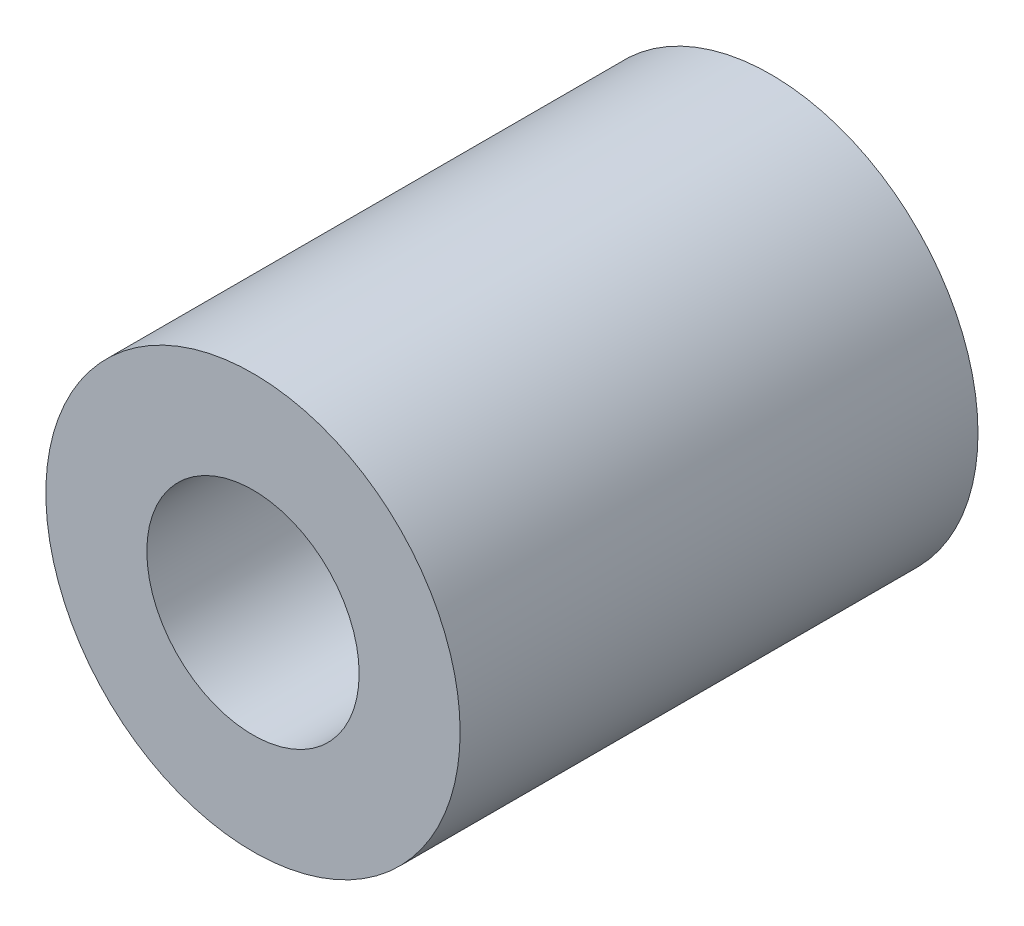
SolidWorks part; units mm, degrees
ref_plane "Płaszczyzna przednia" through (0, 0, 0) normal (0, 0, 1) x (1, 0, 0)
ref_plane "Płaszczyzna górna" through (0, 0, 0) normal (0, 1, 0) x (1, 0, 0)
ref_plane "Płaszczyzna prawa" through (0, 0, 0) normal (1, 0, 0) x (0, 0, -1)
sketch "Szkic1" plane through (0, 0, 0) normal (0, 0, 1) x (1, 0, 0)
  circle A0 centre (170.3, 97.1843) radius 4
extrude "Dodanie-wyciągnięcie1" add sketch "Szkic1" along normal blind 10
sketch "Szkic2" plane through (0, 0, 10) normal (0, 0, 1) x (1, 0, 0)
  circle A0 centre (170.3, 97.1843) radius 2.05
  dimension "D1" = 4.1
extrude "Wytnij-wyciągnięcie1" cut sketch "Szkic2" against normal blind 10
